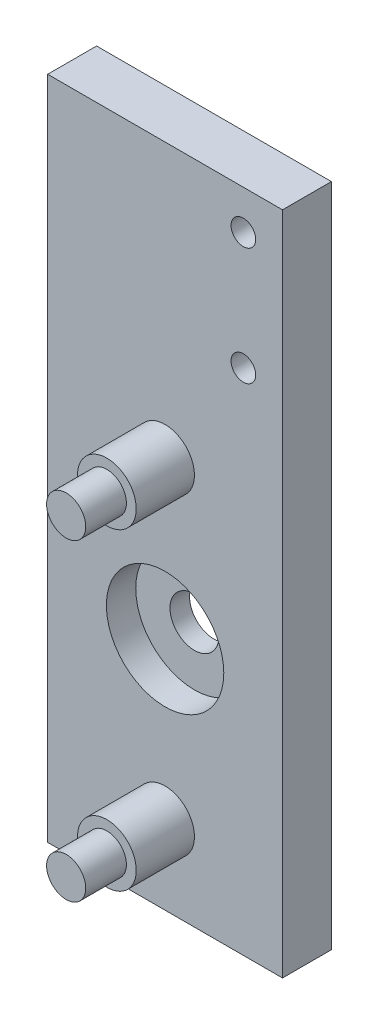
SolidWorks part; units mm, degrees
ref_plane "Front Plane" through (0, 0, 0) normal (0, 0, 1) x (1, 0, 0)
ref_plane "Top Plane" through (0, 0, 0) normal (0, 1, 0) x (1, 0, 0)
ref_plane "Right Plane" through (0, 0, 0) normal (1, 0, 0) x (0, 0, -1)
sketch "Sketch1" plane through (0, 0, 0) normal (0, 0, 1) x (1, 0, 0)
  line L1 (-19.05, -38.1) -> (19.05, -38.1)
  line L2 (-19.05, -38.1) -> (-19.05, 38.1)
  line L3 (-19.05, 38.1) -> (19.05, 38.1)
  line L4 (19.05, -38.1) -> (19.05, 38.1)
  line L5 (-19.05, -38.1) -> (19.05, 38.1) construction
  line L6 (-19.05, 38.1) -> (19.05, -38.1) construction
  point P0 (0, 0)
  dimension "D1" = 38.1
  dimension "D2" = 76.2
extrude "Boss-Extrude1" add sketch "Sketch1" along normal blind 7.9375
sketch "Sketch2" plane through (0, 0, 7.9375) normal (0, 0, 1) x (1, 0, 0)
  circle A0 centre (0, 0) radius 3.9688
  dimension "D1" = 7.9375
extrude "Cut-Extrude1" cut sketch "Sketch2" against normal through all
sketch "Sketch4" plane through (0, 0, 7.9375) normal (0, 0, 1) x (1, 0, 0)
  circle A0 centre (0, 0) radius 9.525
  dimension "D1" = 19.05
extrude "Cut-Extrude2" cut sketch "Sketch4" against normal offset from surface (4.7625 mm away) 3.175 up to face at (3.9688, 0, 0)
sketch "Sketch5" plane through (0, 0, 7.9375) normal (0, 0, 1) x (1, 0, 0)
  line L0 (19.05, 38.1) -> (-19.05, 38.1) construction
  circle A0 centre (0, 25.4) radius 4.7625
  dimension "D1" = 9.525
  dimension "D2" = 12.7
extrude "Boss-Extrude2" add sketch "Sketch5" along normal blind 9.4488
sketch "Sketch6" plane through (0, 0, 17.3863) normal (0, 0, 1) x (1, 0, 0)
  circle A0 centre (0, 25.4) radius 3.175
  dimension "D1" = 6.35
extrude "Boss-Extrude3" add sketch "Sketch6" along normal blind 6.604
mirror "Mirror1" about plane through (0, 0, 0) normal (0, 1, 0) of "Boss-Extrude2", "Boss-Extrude3"
sketch "Sketch7" plane through (0, 0, 7.9375) normal (0, 0, 1) x (1, 0, 0)
  line L0 (19.05, -38.1) -> (19.05, 38.1) construction
  line L1 (-19.05, 38.1) -> (19.05, 38.1)
  line L2 (-19.05, 38.1) -> (-19.05, 69.85)
  line L3 (-19.05, 69.85) -> (19.05, 69.85)
  line L4 (19.05, 38.1) -> (19.05, 69.85)
  line L5 (-19.05, 53.975) -> (19.05, 53.975) construction
  line L6 (12.7, 69.85) -> (12.7, 38.1) construction
  circle A0 centre (12.7, 63.5) radius 2
  circle A1 centre (12.7, 44.45) radius 2
  point P13 (0, 0)
  point P14 (0, 0)
  point P17 (12.7, 63.5)
  dimension "D4" = 4
  dimension "D1" = 31.75
  dimension "D2" = 9.525
  dimension "D3" = 6.35
extrude "Boss-Extrude4" add sketch "Sketch7" against normal up to surface (7.9375 mm away) up to face at (3.9688, 0, 0)
